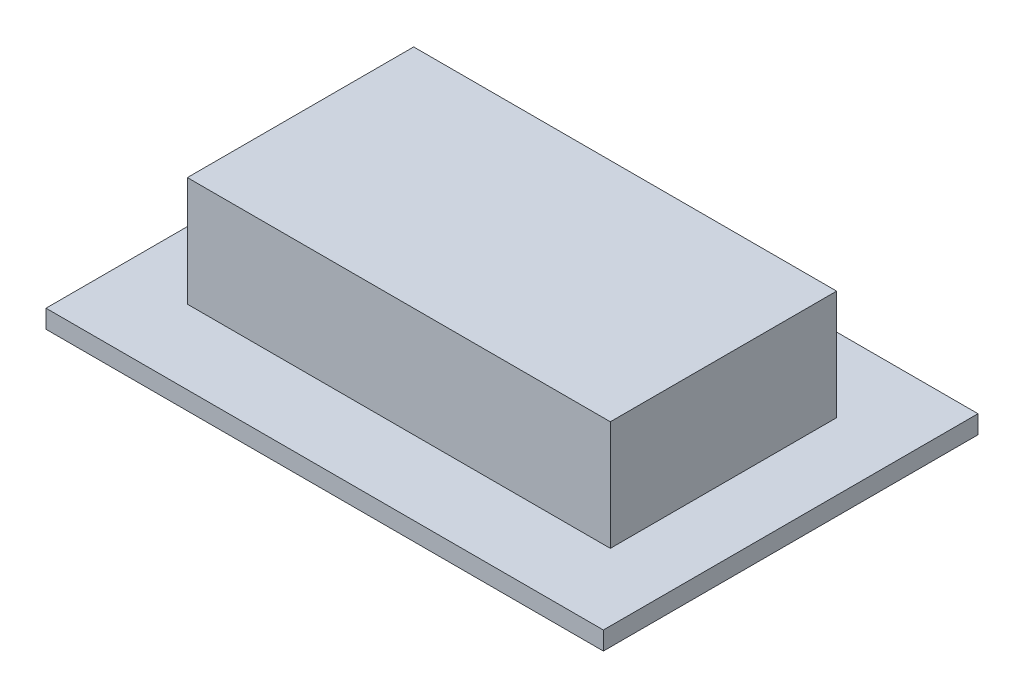
SolidWorks part; units mm, degrees
ref_plane "Front Plane" through (0, 0, 0) normal (0, 0, 1) x (1, 0, 0)
ref_plane "Top Plane" through (0, 0, 0) normal (0, 1, 0) x (1, 0, 0)
ref_plane "Right Plane" through (0, 0, 0) normal (1, 0, 0) x (0, 0, -1)
sketch "Sketch1" plane through (0, 0, 0) normal (0, 1, 0) x (1, 0, 0)
  line L1 (-30.5, -20.5) -> (30.5, -20.5)
  line L2 (-30.5, -20.5) -> (-30.5, 20.5)
  line L3 (-30.5, 20.5) -> (30.5, 20.5)
  line L4 (30.5, -20.5) -> (30.5, 20.5)
  line L5 (-30.5, -20.5) -> (30.5, 20.5) construction
  line L6 (-30.5, 20.5) -> (30.5, -20.5) construction
  point P0 (0, 0)
  dimension "D1" = 41
  dimension "D2" = 61
extrude "Boss-Extrude1" add sketch "Sketch1" along normal blind 2
sketch "Sketch2" plane through (0, 2, 0) normal (0, 1, 0) x (1, 0, 0)
  line L1 (-23.1442, 12.3835) -> (23.1442, 12.3835)
  line L2 (-23.1442, 12.3835) -> (-23.1442, -12.3835)
  line L3 (-23.1442, -12.3835) -> (23.1442, -12.3835)
  line L4 (23.1442, 12.3835) -> (23.1442, -12.3835)
  line L5 (-23.1442, 12.3835) -> (23.1442, -12.3835) construction
  line L6 (-23.1442, -12.3835) -> (23.1442, 12.3835) construction
  point P0 (0, 0)
extrude "Boss-Extrude2" add sketch "Sketch2" along normal blind 12
sketch "Sketch3" plane through (0, 0, 0) normal (0, -1, 0) x (1, 0, 0)
  line L1 (-10.2643, 7.4701) -> (10.2643, 7.4701)
  line L2 (-10.2643, 7.4701) -> (-10.2643, -7.4701)
  line L3 (-10.2643, -7.4701) -> (10.2643, -7.4701)
  line L4 (10.2643, 7.4701) -> (10.2643, -7.4701)
  line L5 (-10.2643, 7.4701) -> (10.2643, -7.4701) construction
  line L6 (-10.2643, -7.4701) -> (10.2643, 7.4701) construction
  point P0 (0, 0)
extrude "Boss-Extrude3" add sketch "Sketch3" along normal blind 12
